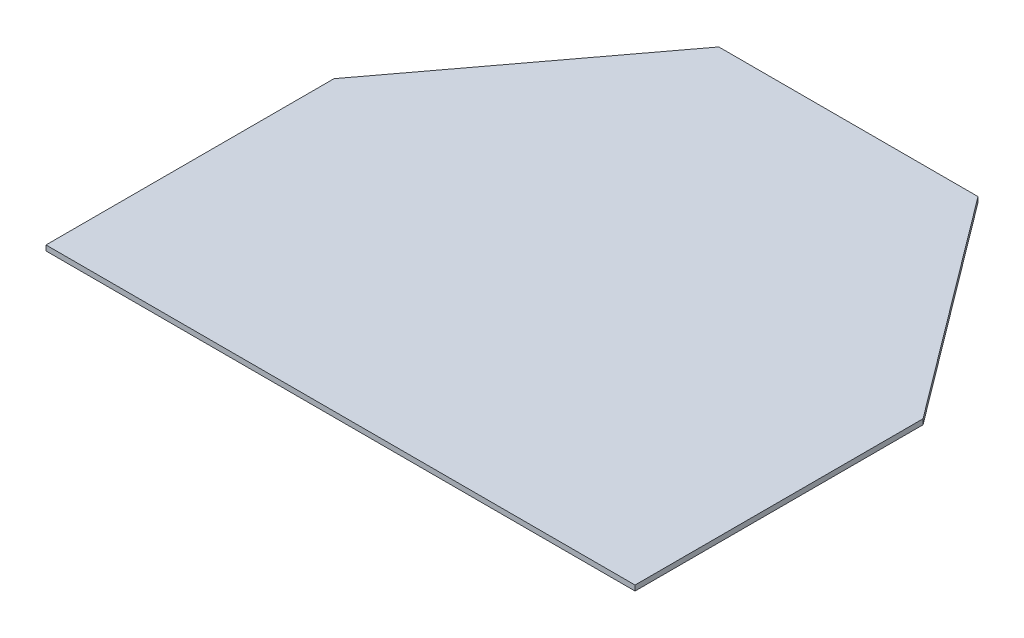
SolidWorks part; units mm, degrees
material "ABS PC"
ref_plane "前视基准面" through (0, 0, 0) normal (0, 0, 1) x (1, 0, 0)
ref_plane "上视基准面" through (0, 0, 0) normal (0, 1, 0) x (1, 0, 0)
ref_plane "右视基准面" through (0, 0, 0) normal (1, 0, 0) x (0, 0, -1)
sketch "草图1" plane through (0, 0, 0) normal (0, 1, 0) x (1, 0, 0)
  line L0 (0, 0) -> (0, 388) construction
  line L1 (-225, 0) -> (225, 0)
  line L2 (225, 0) -> (225, 220)
  line L3 (225, 220) -> (99, 388)
  line L4 (99, 388) -> (-99, 388)
  line L5 (-225, 0) -> (-225, 220)
  line L6 (-225, 220) -> (-99, 388)
  line L7 (0, 388) -> (309, 388) construction
  line L8 (0, 0) -> (445, 0) construction
  circle A0 centre (99, 388) radius 210 construction
  circle A1 centre (225, 0) radius 220 construction
  point P8 (0, 0)
  dimension "D1" = 198
  dimension "D2" = 220
  dimension "D3" = 388
  dimension "D4" = 450
  dimension "D5" = 210
extrude "凸台-拉伸1" add sketch "草图1" along normal blind 4
sketch "草图2" [suppressed] plane through (0, 4, 0) normal (0, 1, 0) x (1, 0, 0)
  line L0 (0, 0) -> (0, 400) construction
  line L1 (90, 400) -> (-90, 400) construction
  line L2 (225, 0) -> (229, 0)
  line L3 (229, 0) -> (229, 221.3333)
  line L4 (229, 221.3333) -> (92, 404)
  line L5 (92, 404) -> (-92, 404)
  line L7 (-90, 400) -> (90, 400)
  line L8 (90, 400) -> (225, 220)
  line L9 (225, 220) -> (225, 0)
  line L10 (-225, 220) -> (-225, 0)
  line L11 (-90, 400) -> (-225, 220)
  line L12 (-229, 221.3333) -> (-92, 404)
  line L13 (-229, 0) -> (-229, 221.3333)
  line L14 (-225, 0) -> (-229, 0)
  dimension "D1" = 4
  dimension "D2" = 4
  dimension "D3" = 4
extrude "凸台-拉伸2" [suppressed] add sketch "草图2" against normal up to surface (4 mm away)
